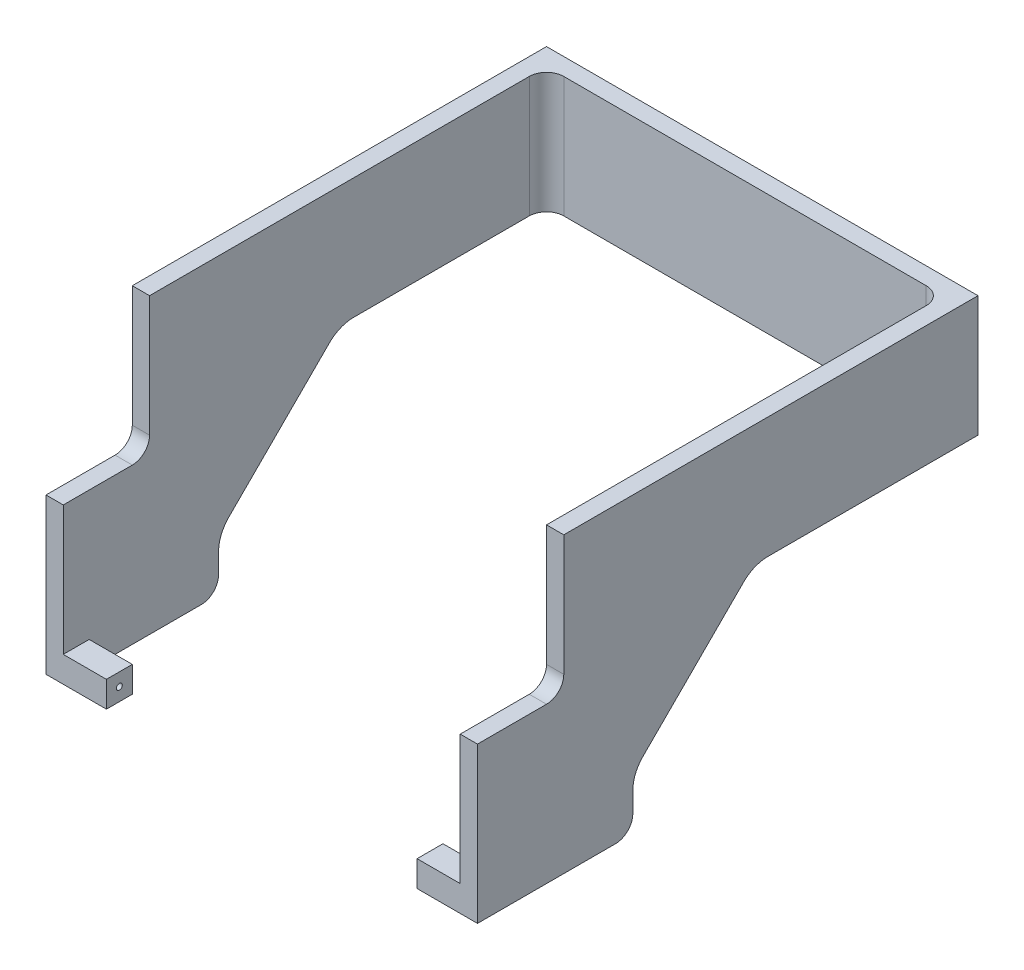
SolidWorks part; units mm, degrees
ref_plane "前视基准面" through (0, 0, 0) normal (0, 0, 1) x (1, 0, 0)
ref_plane "上视基准面" through (0, 0, 0) normal (0, 1, 0) x (1, 0, 0)
ref_plane "右视基准面" through (0, 0, 0) normal (1, 0, 0) x (0, 0, -1)
sketch "草图1" plane through (0, 0, 0) normal (0, 0, 1) x (1, 0, 0)
  line L1 (-125, -85) -> (125, -85)
  line L2 (-125, -85) -> (-125, 85)
  line L3 (-125, 85) -> (125, 85)
  line L4 (125, -85) -> (125, 85)
  line L5 (-125, -85) -> (125, 85) construction
  line L6 (-125, 85) -> (125, -85) construction
  point P0 (0, 0)
  dimension "D1" = 250
  dimension "D2" = 170
extrude "凸台-拉伸1" add sketch "草图1" along normal blind 10
sketch "草图2" plane through (0, 0, 10) normal (0, 0, 1) x (1, 0, 0)
  line L0 (-125, -85) -> (125, -85) construction
  line L1 (-125, 85) -> (-115, 85)
  line L2 (-125, 85) -> (-125, -85)
  line L3 (-125, -85) -> (-115, -85)
  line L4 (-115, 85) -> (-115, -85)
  line L5 (125, 85) -> (-125, 85) construction
  line L6 (115, 85) -> (125, 85)
  line L7 (115, 85) -> (115, -85)
  line L8 (115, -85) -> (125, -85)
  line L9 (125, 85) -> (125, -85)
  dimension "D1" = 10
  dimension "D2" = 10
extrude "凸台-拉伸2" add sketch "草图2" along normal blind 280
sketch "草图3" plane through (-115, 0, 0) normal (1, 0, 0) x (0, 0, -1)
  line L1 (-290, -85) -> (-275, -85)
  line L2 (-290, -85) -> (-290, -70)
  line L3 (-290, -70) -> (-275, -70)
  line L4 (-275, -85) -> (-275, -70)
  dimension "D1" = 15
  dimension "D2" = 15
extrude "凸台-拉伸3" add sketch "草图3" along normal blind 25
sketch "草图4" plane through (115, 0, 0) normal (-1, 0, 0) x (0, 0, 1)
  line L0 (290, 85) -> (290, -85) construction
  line L1 (290, -85) -> (275, -85)
  line L2 (290, -85) -> (290, -70)
  line L3 (290, -70) -> (275, -70)
  line L4 (275, -85) -> (275, -70)
  point P6 (205, -75)
  dimension "D1" = 15
  dimension "D2" = 15
extrude "凸台-拉伸4" add sketch "草图4" along normal blind 25
sketch "草图5" plane through (90, 0, 0) normal (-1, 0, 0) x (0, 0, 1)
  line L0 (275, -70) -> (290, -85) construction
  line L1 (290, -70) -> (275, -85) construction
  circle A0 centre (282.5, -77.5) radius 1.7
  dimension "D1" = 3.4
extrude "切除-拉伸1" cut sketch "草图5" against normal blind 5
sketch "草图6" plane through (-90, 0, 0) normal (1, 0, 0) x (0, 0, -1)
  line L0 (-290, -70) -> (-275, -85) construction
  line L1 (-275, -70) -> (-290, -85) construction
  circle A0 centre (-282.5, -77.5) radius 1.7
  dimension "D1" = 3.4
extrude "切除-拉伸2" cut sketch "草图6" against normal blind 5
sketch "草图7" plane through (0, 0, 0) normal (0, 0, -1) x (-1, 0, 0)
  line L0 (125, 85) -> (125, -85) construction
  line L1 (-125, -85) -> (125, -85)
  line L2 (-125, -85) -> (-125, 15)
  line L3 (-125, 15) -> (125, 15)
  line L4 (125, -85) -> (125, 15)
  dimension "D1" = 100
extrude "切除-拉伸3" cut sketch "草图7" against normal blind 200
sketch "草图8" plane through (0, 0, 290) normal (0, 0, 1) x (1, 0, 0)
  line L0 (125, -85) -> (125, 85) construction
  line L1 (-125, 85) -> (125, 85)
  line L2 (-125, 85) -> (-125, 5)
  line L3 (-125, 5) -> (125, 5)
  line L4 (125, 85) -> (125, 5)
  dimension "D1" = 80
extrude "切除-拉伸4" cut sketch "草图8" against normal blind 50
fillet "圆角1" radius 10 6 edges at (120, -85, 200) (120, 5, 240) (-120, -85, 200) (-120, 5, 240) (-115, 50, 10) (115, 50, 10)
chamfer "倒角2" distance 70 angle 45 2 edges at (-120, 15, 200) (120, 15, 200)
fillet "圆角3" radius 20 4 edges at (-120, -55, 200) (-120, 15, 130) (120, 15, 130) (120, -55, 200)
